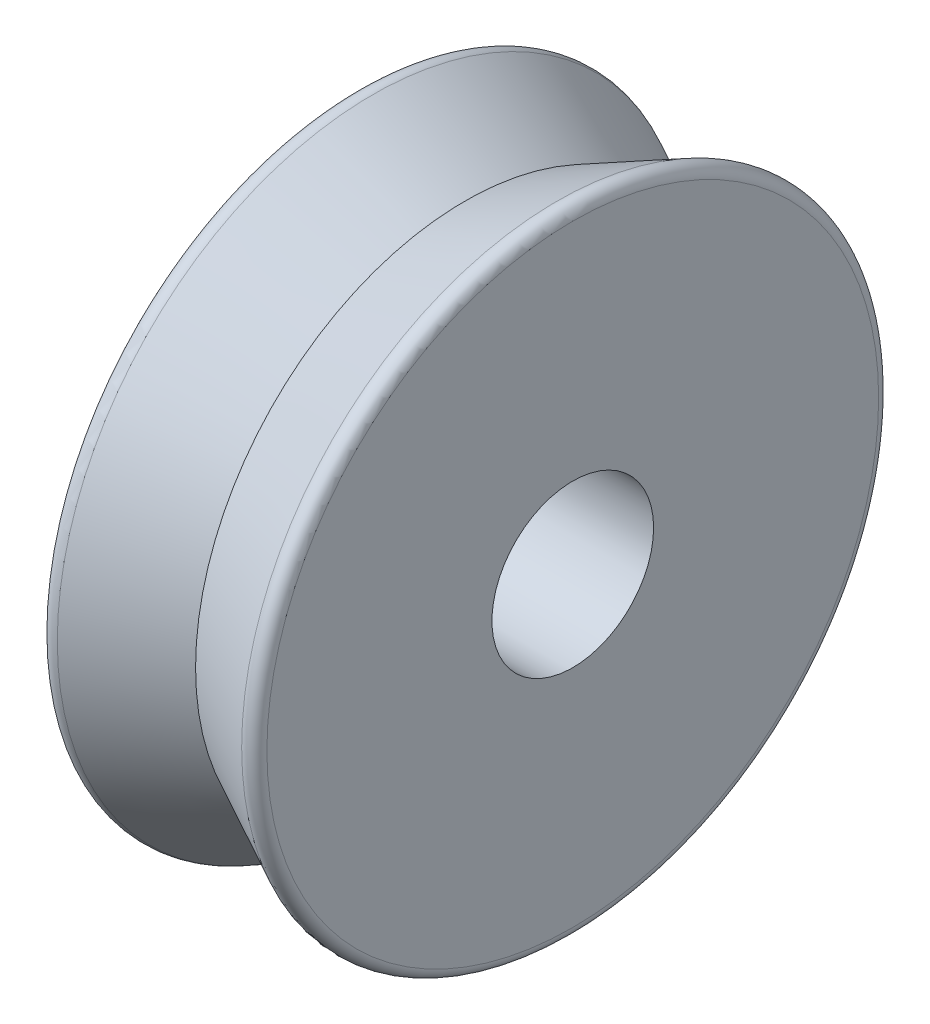
SolidWorks part; units mm, degrees
ref_plane "Front Plane" through (0, 0, 0) normal (0, 0, 1) x (1, 0, 0)
ref_plane "Top Plane" through (0, 0, 0) normal (0, 1, 0) x (1, 0, 0)
ref_plane "Right Plane" through (0, 0, 0) normal (1, 0, 0) x (0, 0, -1)
sketch "Sketch1" plane through (0, 0, 0) normal (0, 0, 1) x (1, 0, 0)
  line L0 (-9.7938, 0) -> (10.1287, 0) construction
  line L1 (0, 11.0281) -> (0, -8.3405) construction
  line L2 (0, 5) -> (-2, 6)
  line L3 (-2, 6) -> (-2, 0)
  line L4 (2, 6) -> (2, 0)
  line L5 (0, 5) -> (2, 6)
  line L6 (-2, 0) -> (2, 0)
  dimension "D1" = 2
  dimension "D2" = 6
  dimension "D3" = 1
revolve "Revolve1" add sketch "Sketch1" angle 360 about L0
sketch "Sketch2" plane through (0, 0, 0) normal (1, 0, 0) x (0, 0, -1)
  circle A0 centre (0, 0) radius 1.5
  dimension "D1" = 3
extrude "Cut-Extrude1" cut sketch "Sketch2" against normal through all both and the other way through all
fillet "Fillet2" radius 0.2 2 edges at (2, 0, 6) (-2, 0, 6)
